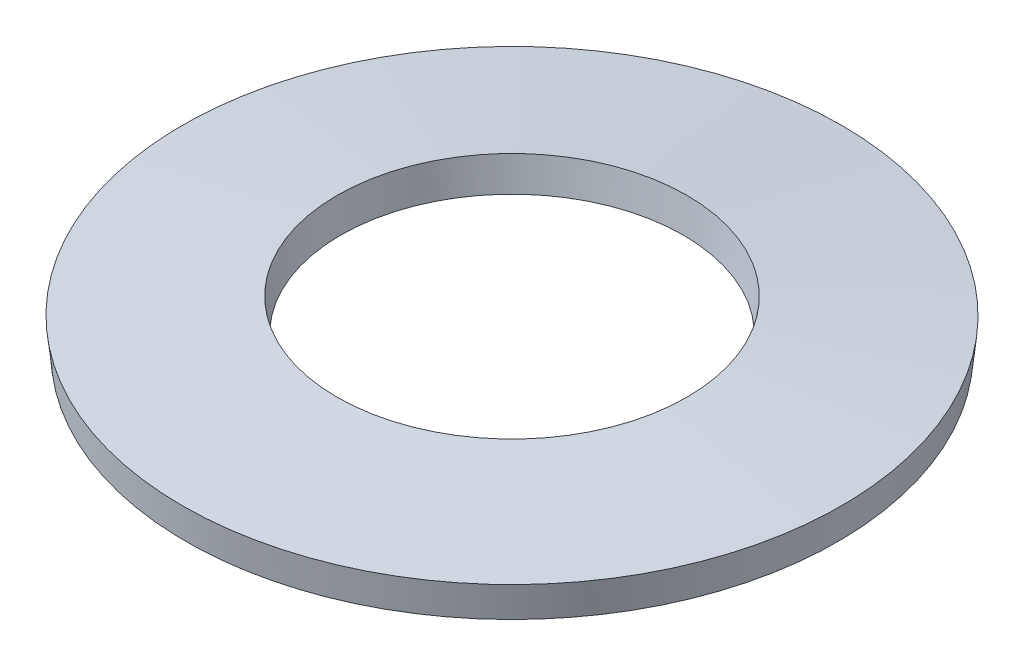
SolidWorks part; units mm, degrees
ref_plane "Front" through (0, 0, 0) normal (0, 0, 1) x (1, 0, 0)
ref_plane "Top" through (0, 0, 0) normal (0, 1, 0) x (1, 0, 0)
ref_plane "Right" through (0, 0, 0) normal (1, 0, 0) x (0, 0, -1)
sketch "Sketch1" plane through (0, 0, 0) normal (0, 0, 1) x (1, 0, 0)
  line L0 (4.9464, 0) -> (2.6, 0.2529)
  line L1 (2.6, 0.2529) -> (2.6536, 0.75)
  line L2 (2.6536, 0.75) -> (5, 0.4971)
  line L3 (5, 0.4971) -> (4.9464, 0)
  line L4 (0, 0) -> (0, 0.75) construction
  dimension "ID" = 5.2
  dimension "OD" = 10
  dimension "Thickness" = 0.5
  dimension "Height" = 0.75
revolve "Revolve1" add sketch "Sketch1" angle 360 about L4
